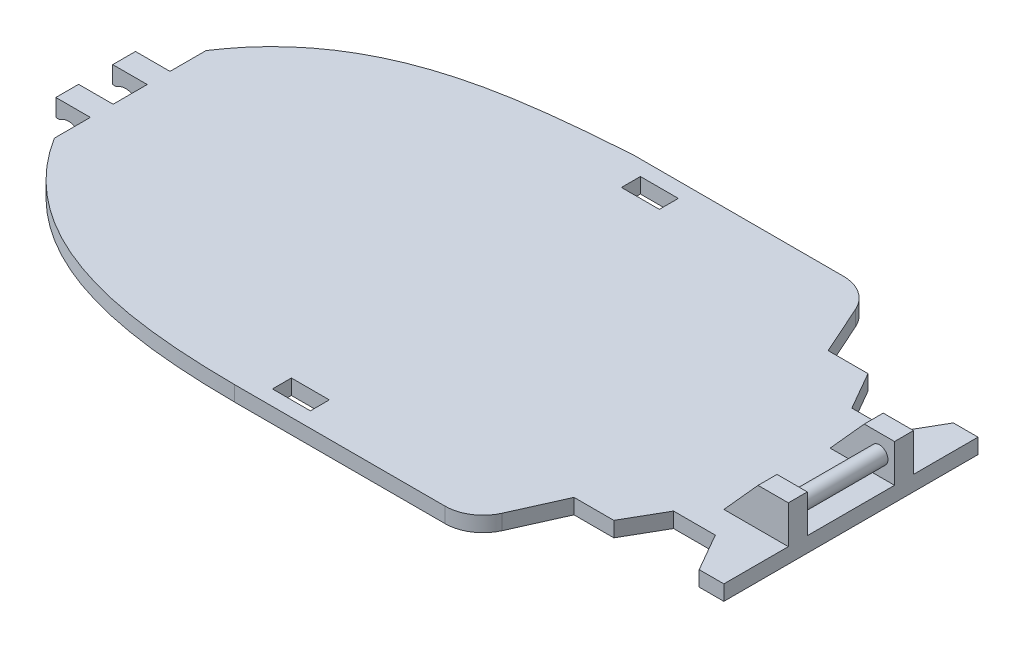
SolidWorks part; units mm, degrees
ref_plane "Front Plane" through (0, 0, 0) normal (0, 0, 1) x (1, 0, 0)
ref_plane "Top Plane" through (0, 0, 0) normal (0, 1, 0) x (1, 0, 0)
ref_plane "Right Plane" through (0, 0, 0) normal (1, 0, 0) x (0, 0, -1)
sketch "Sketch1" plane through (0, 0, 0) normal (0, 1, 0) x (1, 0, 0)
  line L0 (-110, 0) -> (0, 0)
  line L1 (0, 0) -> (0, -105)
  line L2 (0, -105) -> (-110, -105)
  line L4 (-190, -72.5) -> (-190, -32.5)
  spline S0 degree 3 poles (-190, -32.5) (-171.7074, -4.6189) (-138.9899, -2.1787) (-110, 0) knots 0 0 0 0 1 1 1 1
  spline S1 degree 2 poles (-190.0397, -35.2371) (-187.6331, -30.2964) (-183.9056, -25.9107) (-180.479, -21.8792) (-175.9528, -18.3354) (-171.8462, -15.1201) (-166.8566, -12.3231) (-164.564, -11.0379) (-162.0905, -9.8442) (-159.6124, -8.6482) (-157.2765, -7.6915) knots 0 0 0 0.25 0.25 0.5 0.5 0.75 0.75 0.875 0.875 1 1 1 construction
  spline S2 degree 2 poles (-157.2765, -7.6915) (-155.8569, -7.11) (-154.4721, -6.6099) (-153.0466, -6.0951) (-151.6197, -5.6536) (-148.8172, -4.7863) (-145.7427, -4.1123) (-142.8487, -3.4777) (-139.6519, -3.0009) (-136.688, -2.5589) (-133.369, -2.2385) knots 0 0 0 0.125 0.125 0.25 0.25 0.5 0.5 0.75 0.75 1 1 1 construction
  spline S3 degree 3 poles (-190, -72.5) (-172.2628, -100.7004) (-139.266, -104.8361) (-110, -105) knots 0 0 0 0 1 1 1 1
  point P11 (-190, -52.5)
  point P12 (0, -52.5)
  dimension "D4" = 40
  dimension "D1" = 110
  dimension "D2" = 105
  dimension "D3" = 190
  dimension "D5" = 110
extrude "Boss-Extrude1" add sketch "Sketch1" along normal blind 4
sketch "Sketch2" plane through (0, 0, 105) normal (0, 0, 1) x (1, 0, 0)
  line L0 (-190, 4) -> (-201, 4)
  line L1 (-178, 0) -> (-191, -11)
  line L2 (57.75, 0) -> (-57.75, 0) construction
  line L3 (-191, -11) -> (-201, -11)
  line L6 (-190, 4) -> (-178, 0)
  line L7 (-201, 4) -> (-201, -11)
  dimension "D1" = 11
  dimension "D2" = 15
  dimension "D5" = 10
extrude "Boss-Extrude2" add sketch "Sketch2" along normal mid plane 6 from offset 45 offset against normal yes
ref_plane "Plane1" through (0, 0, 52.5) normal (0, 0, 1) x (1, 0, 0)
mirror "Mirror1" about plane through (0, 0, 52.5) normal (0, 0, 1) of "Boss-Extrude2"
ref_plane "Plane2" through (-100, 0, 0) normal (1, 0, 0) x (0, 0, -1)
sketch "Sketch5" plane through (0, 0, 105) normal (0, 0, 1) x (1, 0, 0)
  line L0 (-16.9798, 4) -> (-7.9798, 14)
  line L1 (-110, 4) -> (0, 4) construction
  line L2 (-7.9798, 14) -> (0, 14)
  line L3 (0, 14) -> (0, 4)
  line L4 (0, 4) -> (-16.9798, 4)
  dimension "D1" = 10
  dimension "D2" = 9
extrude "Boss-Extrude3" add sketch "Sketch5" along direction (0, 0, 1) on the side against the normal mid plane 6 from offset 39 contours L2 L3 L4 L0 offset against normal yes
mirror "Mirror4" about plane through (0, 0, 52.5) normal (0, 0, 1) of "Boss-Extrude3"
sketch "Sketch6" plane through (0, 0, 42) normal (0, 0, 1) x (1, 0, 0)
  line L0 (0, -2.2) -> (0, 2.2) construction
  line L1 (-110, 4) -> (0, 4) construction
  circle A0 centre (-4, 10) radius 2.5
  dimension "D1" = 5
  dimension "D2" = 4
  dimension "D3" = 6
extrude "Boss-Extrude4" add sketch "Sketch6" along normal up to body separate body
sketch "Sketch7" plane through (0, 4, 0) normal (0, 1, 0) x (1, 0, 0)
  line L0 (-110, -105) -> (0, -105) construction
  line L1 (-104, -101) -> (-94, -101)
  line L2 (-104, -101) -> (-104, -96)
  line L3 (-104, -96) -> (-94, -96)
  line L4 (-94, -101) -> (-94, -96)
  dimension "D1" = 6
  dimension "D2" = 10
  dimension "D3" = 5
  dimension "D4" = 4
extrude "Cut-Extrude1" cut sketch "Sketch7" against normal blind 10
mirror "Mirror5" about plane through (0, 0, 52.5) normal (0, 0, 1) of "Cut-Extrude1"
sketch "Sketch8" plane through (0, 4, 0) normal (0, 1, 0) x (1, 0, 0)
  line L0 (-13.75, -52.5) -> (13.75, -52.5) construction
  line L1 (-190, -48) -> (-190, -57) construction
  circle A0 centre (-150, -52.5) radius 7.5
  dimension "D2" = 15
  dimension "D1" = 40
sketch "Sketch9" plane through (0, 0, 52.5) normal (0, 0, 1) x (1, 0, 0)
  line L0 (-150, 4) -> (-163.8674, -3.4662)
  line L1 (-142.5, 4) -> (-157.5, 4) construction
sketch "Sketch10" plane through (0, 4, 0) normal (0, 1, 0) x (1, 0, 0)
  line L0 (0, -19) -> (-39.5, -19)
  line L1 (0, -2.2) -> (0, 2.2) construction
  line L2 (-39.5, -19) -> (-48, 0)
  line L3 (-2.2, 0) -> (2.2, 0) construction
  line L4 (-48, 0) -> (0, 0)
  line L5 (0, 0) -> (0, -19)
  dimension "D1" = 19
  dimension "D2" = 8.5
  dimension "D3" = 48
extrude "Cut-Extrude2" cut sketch "Sketch10" against normal through all both and the other way through all contours L2 L4 L5 L0
mirror "Mirror6" about plane through (0, 0, 52.5) normal (0, 0, 1) of "Cut-Extrude2"
fillet "Fillet1" radius 10 2 edges at (-48, 2, 0) (-48, 2, 105)
sketch "Sketch11" plane through (0, 4, 0) normal (0, 1, 0) x (1, 0, 0)
  line L0 (-6.5, -19) -> (-12.25, -29)
  line L1 (0, -19) -> (-39.5, -19) construction
  line L2 (-12.25, -29) -> (-23.25, -29)
  line L3 (-23.25, -29) -> (-29, -19)
  line L4 (-29, -19) -> (-6.5, -19)
  line L6 (0, -13.75) -> (0, 13.75) construction
  point P9 (-17.75, -19)
  point P10 (-17.75, -29)
  dimension "D1" = 6.5
  dimension "D2" = 10.5
  dimension "D3" = 10
  dimension "D4" = 11
extrude "Cut-Extrude3" cut sketch "Sketch11" against normal through all both and the other way through all
mirror "Mirror7" about plane through (0, 0, 52.5) normal (0, 0, 1) of "Cut-Extrude3"
sketch "Sketch12" plane through (0, 0, 0) normal (1, 0, 0) x (0, 0, -1)
  line L0 (-63, 14) -> (-64, 14) construction
  line L1 (-69, 14) -> (-63, 14) construction
  line L2 (-42, 14) -> (-41, 14) construction
  line L3 (-36, 14) -> (-42, 14) construction
  line L4 (-41, 14) -> (-41, 3.5219) construction
  line L5 (-42, 4) -> (-38.9627, 4) construction
  line L7 (-64, 14) -> (-41, 14)
  line L8 (-64, 14) -> (-64, 4)
  line L9 (-64, 4) -> (-41, 4)
  line L10 (-41, 14) -> (-41, 4)
extrude "Cut-Extrude6" cut sketch "Sketch12" against normal blind 21
sketch "Sketch13" plane through (0, 0, 64) normal (0, 0, -1) x (-1, 0, 0)
  line L0 (7.9798, 14) -> (7.9798, 4.2522) construction
  line L1 (0, 14) -> (7.9798, 4) construction
  line L2 (0, 13.75) -> (0, -13.75) construction
  line L3 (7.9798, 14) -> (0, 14) construction
  line L4 (0, 4) -> (6.5, 4) construction
  line L5 (0, 4) -> (7.9798, 14) construction
  circle A0 centre (3.9899, 9) radius 2.25
  dimension "D1" = 4.5
extrude "Boss-Extrude5" add sketch "Sketch13" along normal up to next
sketch "Sketch14" plane through (0, 0, 52.5) normal (0, 0, 1) x (1, 0, 0)
  line L0 (-201, 4) -> (-201, -11) construction
  line L1 (-201, 4) -> (-201, -11) construction
  line L2 (-190, 4) -> (-201, -11) construction
  line L4 (-201, 4) -> (-191, -11) construction
  line L5 (-198.0957, 4) -> (-198.0957, -0.5654)
  line L6 (-190, 4) -> (-201, 4) construction
  line L7 (-201, -11) -> (-191, -11) construction
  line L8 (-198.0957, -11) -> (-202.7192, -12.1152)
  line L9 (-202.7192, -12.1152) -> (-202.5885, 4.843)
  line L10 (-202.5885, 4.843) -> (-198.0957, 4)
  line L11 (-198.0957, -6.9618) -> (-198.0957, -11)
  arc A0 (-198.0957, -6.9618) -> (-198.0957, -0.5654) centre (-195.6933, -3.7636) ccw
extrude "Cut-Extrude7" cut sketch "Sketch14" against normal through all both and the other way through all
sketch "Sketch15" plane through (-198.0957, 0, 0) normal (-1, 0, 0) x (0, 0, 1)
  line L4 (63, 4) -> (57, 4)
  line L5 (57, 4) -> (57, -0.5654)
  line L6 (57, -0.5654) -> (63, -0.5654)
  line L7 (63, -0.5654) -> (63, 4)
  line L8 (63, 4) -> (57, 4)
  line L9 (57, 4) -> (57, -0.5654)
  line L10 (57, -0.5654) -> (63, -0.5654)
  line L11 (63, -0.5654) -> (63, 4)
  line L12 (42, -0.5654) -> (48, -0.5654)
  line L13 (48, -0.5654) -> (48, 4)
  line L14 (48, 4) -> (42, 4)
  line L15 (42, 4) -> (42, -0.5654)
  line L16 (42, -0.5654) -> (48, -0.5654)
  line L17 (48, -0.5654) -> (48, 4)
  line L18 (48, 4) -> (42, 4)
  line L19 (42, 4) -> (42, -0.5654)
  line L20 (42, -11) -> (48, -11)
  line L21 (48, -11) -> (48, -6.9618)
  line L22 (48, -6.9618) -> (42, -6.9618)
  line L23 (42, -6.9618) -> (42, -11)
  line L24 (42, -11) -> (48, -11)
  line L25 (48, -11) -> (48, -6.9618)
  line L26 (48, -6.9618) -> (42, -6.9618)
  line L27 (42, -6.9618) -> (42, -11)
  line L28 (63, -6.9618) -> (57, -6.9618)
  line L29 (57, -6.9618) -> (57, -11)
  line L30 (57, -11) -> (63, -11)
  line L31 (63, -11) -> (63, -6.9618)
  line L32 (63, -6.9618) -> (57, -6.9618)
  line L33 (57, -6.9618) -> (57, -11)
  line L34 (57, -11) -> (63, -11)
  line L35 (63, -11) -> (63, -6.9618)
  dimension "D1" = 0
  dimension "D2" = 0
  dimension "D3" = 0
  dimension "D4" = 0
extrude "Boss-Extrude6" add sketch "Sketch15" along normal blind 1
